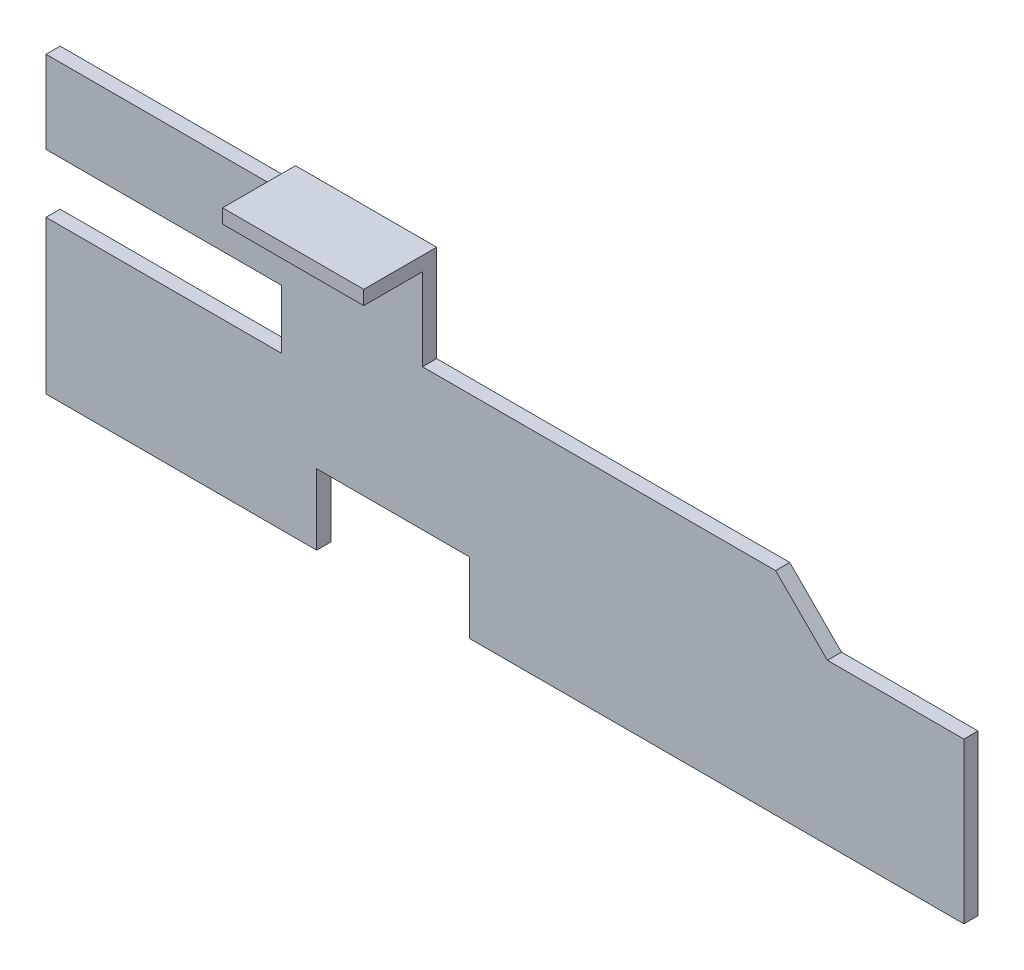
SolidWorks part; units mm, degrees
material "铜"
ref_plane "前视基准面" through (0, 0, 0) normal (0, 0, 1) x (1, 0, 0)
ref_plane "上视基准面" through (0, 0, 0) normal (0, 1, 0) x (1, 0, 0)
ref_plane "右视基准面" through (0, 0, 0) normal (1, 0, 0) x (0, 0, -1)
sketch "草图1" plane through (0, 0, 0) normal (0, 0, 1) x (1, 0, 0)
  line L0 (0, 0) -> (11.5, 0)
  line L1 (11.5, 0) -> (11.5, 3)
  line L2 (11.5, 3) -> (18, 3)
  line L3 (18, 3) -> (18, 0)
  line L4 (18, 0) -> (39, 0)
  line L5 (39, 0) -> (39, 6.8)
  line L6 (39, 6.8) -> (33.2, 6.8)
  line L7 (33.2, 6.8) -> (31, 9)
  line L8 (31, 9) -> (16, 9)
  line L9 (16, 9) -> (16, 15)
  line L10 (16, 15) -> (10, 15)
  line L11 (10, 15) -> (10, 12.5)
  line L12 (10, 12.5) -> (0, 12.5)
  line L13 (0, 12.5) -> (0, 9)
  line L14 (0, 9) -> (10, 9)
  line L15 (10, 9) -> (10, 6.5)
  line L16 (10, 6.5) -> (0, 6.5)
  line L17 (0, 6.5) -> (0, 0)
  dimension "D1" = 39
  dimension "D2" = 15
  dimension "D3" = 16
  dimension "D4" = 9
  dimension "D5" = 15
  dimension "D6" = 6.8
  dimension "D7" = 6.5
  dimension "D8" = 11.5
  dimension "D9" = 10
  dimension "D10" = 2.5
  dimension "D11" = 6.5
  dimension "D12" = 3.5
  dimension "D13" = 3
  dimension "D14" = 10
  dimension "D15" = 2.2
extrude "凸台-拉伸1" add sketch "草图1" along normal blind 0.6
sketch "草图2" plane through (0, 0, 0.6) normal (0, 0, 1) x (1, 0, 0)
  line L0 (16, 9) -> (16, 15) construction
  line L2 (10, 12.5) -> (16, 12.5)
  line L3 (10, 12.5) -> (10, 13.1)
  line L4 (10, 13.1) -> (16, 13.1)
  line L5 (16, 12.5) -> (16, 13.1)
  dimension "D1" = 0.6
extrude "凸台-拉伸2" add sketch "草图2" along normal blind 2.5
sketch "草图4" plane through (0, 0, 0.6) normal (0, 0, 1) x (1, 0, 0)
  line L1 (10, 13.1) -> (16, 13.1)
  line L2 (10, 13.1) -> (10, 15)
  line L3 (10, 15) -> (16, 15)
  line L4 (16, 13.1) -> (16, 15)
extrude "切除-拉伸1" cut sketch "草图4" against normal through all
